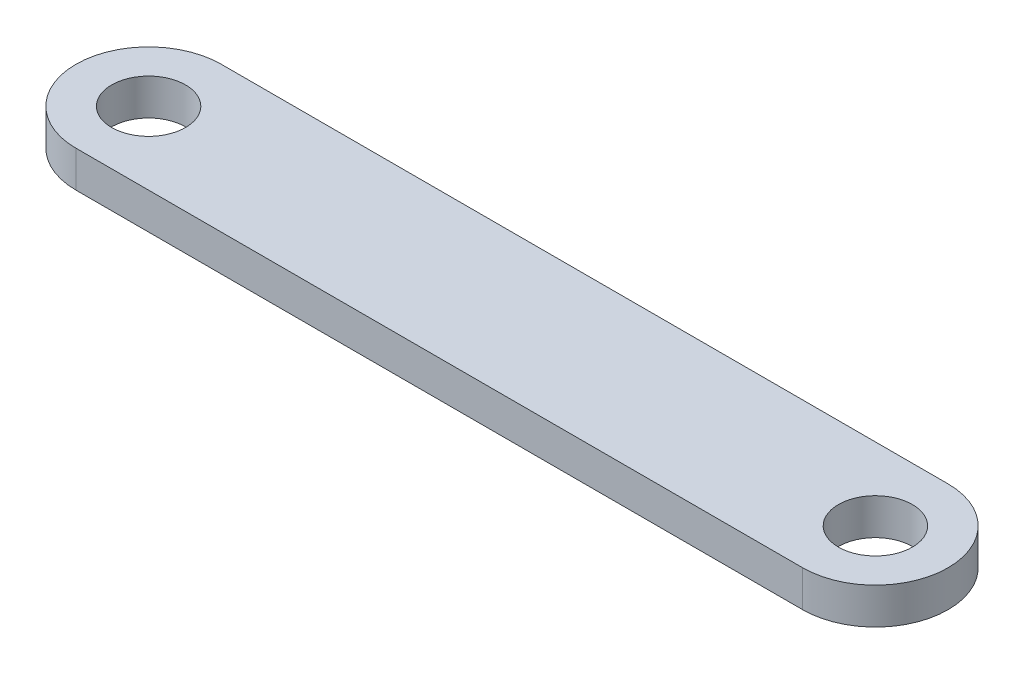
SolidWorks part; units mm, degrees
material "ABS"
ref_plane "Front Plane" through (0, 0, 0) normal (0, 0, 1) x (1, 0, 0)
ref_plane "Top Plane" through (0, 0, 0) normal (0, 1, 0) x (1, 0, 0)
ref_plane "Right Plane" through (0, 0, 0) normal (1, 0, 0) x (0, 0, -1)
sketch "Sketch1" plane through (0, 0, 0) normal (0, 1, 0) x (1, 0, 0)
  line L0 (0, 0) -> (60, 0) construction
  line L1 (-1.65, 0) -> (1.65, 0) construction
  line L2 (0, 6) -> (60, 6)
  line L3 (0, -6) -> (60, -6)
  arc A0 (0, 6) -> (0, -6) centre (0, 0) ccw
  arc A1 (60, -6) -> (60, 6) centre (60, 0) ccw
  circle A2 centre (0, 0) radius 3.05
  circle A3 centre (60, 0) radius 3.05
  point P5 (30, 0)
  dimension "D2" = 12
  dimension "D3" = 6.1
  dimension "D1" = 60
extrude "Boss-Extrude1" add sketch "Sketch1" along normal blind 3
